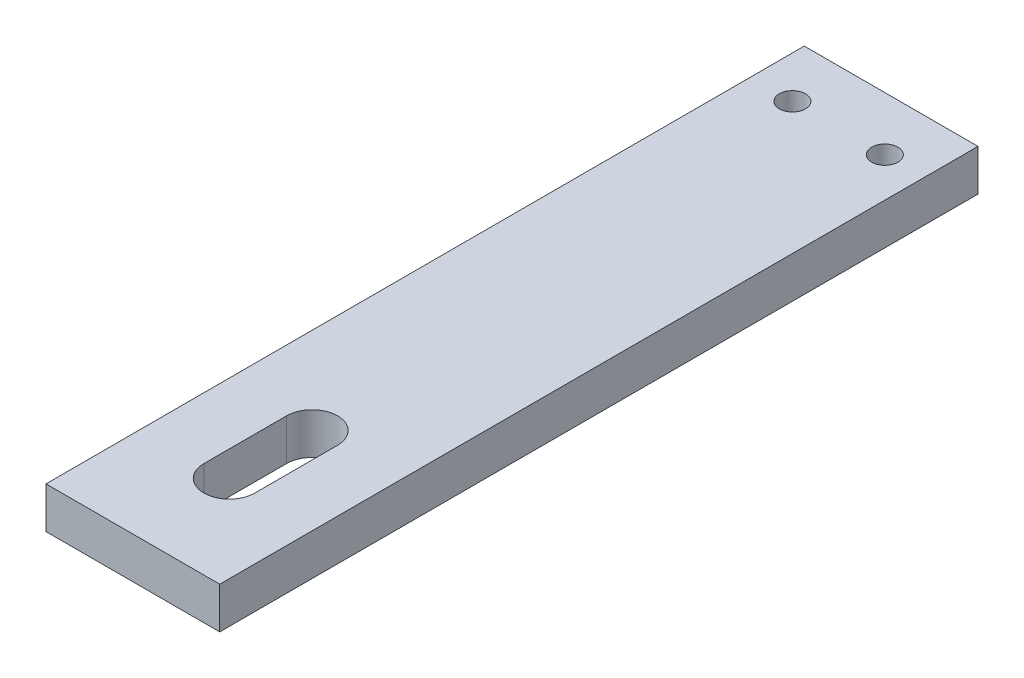
SolidWorks part; units mm, degrees
ref_plane "Front Plane" through (0, 0, 0) normal (0, 0, 1) x (1, 0, 0)
ref_plane "Top Plane" through (0, 0, 0) normal (0, 1, 0) x (1, 0, 0)
ref_plane "Right Plane" through (0, 0, 0) normal (1, 0, 0) x (0, 0, -1)
sketch "Sketch1" plane through (0, 0, 0) normal (0, 1, 0) x (1, 0, 0)
  line L0 (-6.3, 7) -> (-6.3, 13) construction
  line L1 (0, 0) -> (-12.6, 0)
  line L2 (0, 0) -> (0, 55)
  line L3 (0, 55) -> (-12.6, 55)
  line L4 (-12.6, 0) -> (-12.6, 55)
  line L5 (-8.15, 7) -> (-8.15, 13)
  line L6 (-4.45, 7) -> (-4.45, 13)
  arc A0 (-8.15, 7) -> (-4.45, 7) centre (-6.3, 7) ccw
  arc A1 (-4.45, 13) -> (-8.15, 13) centre (-6.3, 13) ccw
  point P7 (-6.3, 10)
  point P12 (-6.3, 55)
  dimension "D1" = 55
  dimension "D2" = 12.6
  dimension "D3" = 3.7
  dimension "D4" = 6
  dimension "D5" = 7
extrude "Boss-Extrude1" add sketch "Sketch1" along normal blind 3
sketch "Sketch2" plane through (0, 0, 0) normal (0, -1, 0) x (1, 0, 0)
  line L0 (0, -55) -> (-12.6, -55) construction
  line L1 (-12.6, -55) -> (-12.6, 0) construction
  circle A0 centre (-2.86, -51.1) radius 0.95
  circle A1 centre (-9.56, -51.1) radius 0.95
  dimension "D4" = 1.9
  dimension "D1" = 6.7
  dimension "D2" = 3.9
  dimension "D3" = 3.04
extrude "Cut-Extrude1" cut sketch "Sketch2" against normal through all
